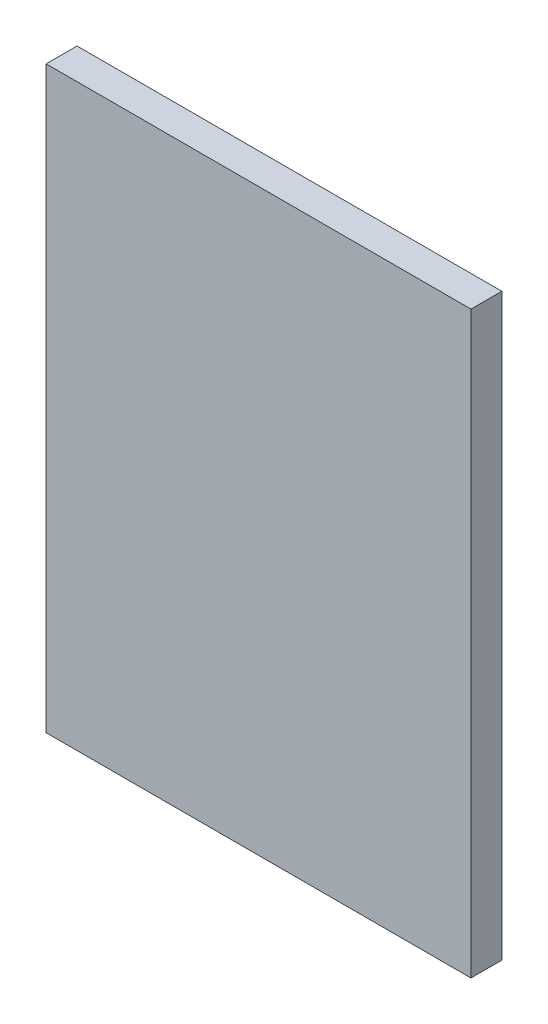
SolidWorks part; units mm, degrees
ref_plane "前视基准面" through (0, 0, 0) normal (0, 0, 1) x (1, 0, 0)
ref_plane "上视基准面" through (0, 0, 0) normal (0, 1, 0) x (1, 0, 0)
ref_plane "右视基准面" through (0, 0, 0) normal (1, 0, 0) x (0, 0, -1)
sketch "草图1" plane through (0, 0, 0) normal (0, 0, 1) x (1, 0, 0)
  line L1 (0, 0) -> (110, 0)
  line L2 (0, 0) -> (0, 150)
  line L3 (0, 150) -> (110, 150)
  line L4 (110, 0) -> (110, 150)
  dimension "D1" = 110
  dimension "D2" = 150
extrude "凸台-拉伸1" add sketch "草图1" along normal blind 8
